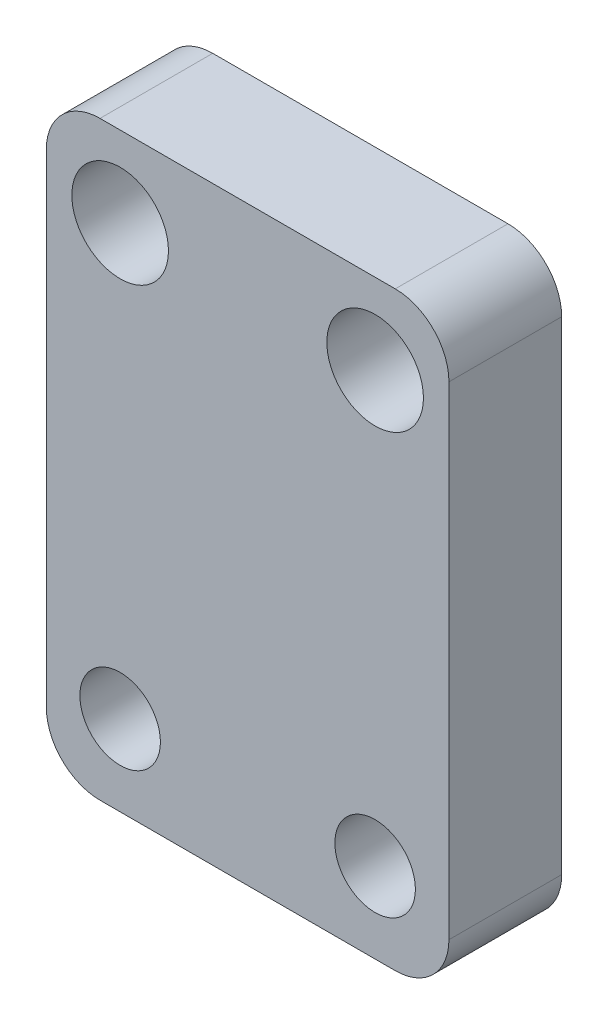
SolidWorks part; units mm, degrees
ref_plane "Front Plane" through (0, 0, 0) normal (0, 0, 1) x (1, 0, 0)
ref_plane "Top Plane" through (0, 0, 0) normal (0, 1, 0) x (1, 0, 0)
ref_plane "Right Plane" through (0, 0, 0) normal (1, 0, 0) x (0, 0, -1)
sketch "Sketch1" plane through (0, 0, 0) normal (0, 0, 1) x (1, 0, 0)
  line L0 (-4.75, 8) -> (4.75, 8) construction
  line L1 (-7.5, -11) -> (7.5, -11)
  line L2 (-7.5, -11) -> (-7.5, 11)
  line L3 (-7.5, 11) -> (7.5, 11)
  line L4 (7.5, -11) -> (7.5, 11)
  line L5 (-7.5, -11) -> (7.5, 11) construction
  line L6 (-7.5, 11) -> (7.5, -11) construction
  line L7 (-4.75, -8) -> (4.75, -8) construction
  circle A0 centre (-4.75, 8) radius 1.8
  circle A1 centre (4.75, 8) radius 1.8
  circle A2 centre (-4.75, -8) radius 1.5
  circle A3 centre (4.75, -8) radius 1.5
  point P0 (0, 0)
  point P14 (0, 8)
  point P15 (0, 11)
  point P16 (0, -8)
  point P17 (0, 0)
  dimension "D4" = 3.6
  dimension "D6" = 3
  dimension "D1" = 15
  dimension "D2" = 22
  dimension "D3" = 9.5
  dimension "D5" = 3
  dimension "D7" = 3
  dimension "D8" = 9.5
extrude "Boss-Extrude1" add sketch "Sketch1" along normal blind 4.2
fillet "Fillet1" radius 2 4 edges at (7.5, -11, 2.1) (-7.5, -11, 2.1) (7.5, 11, 2.1) (-7.5, 11, 2.1)
